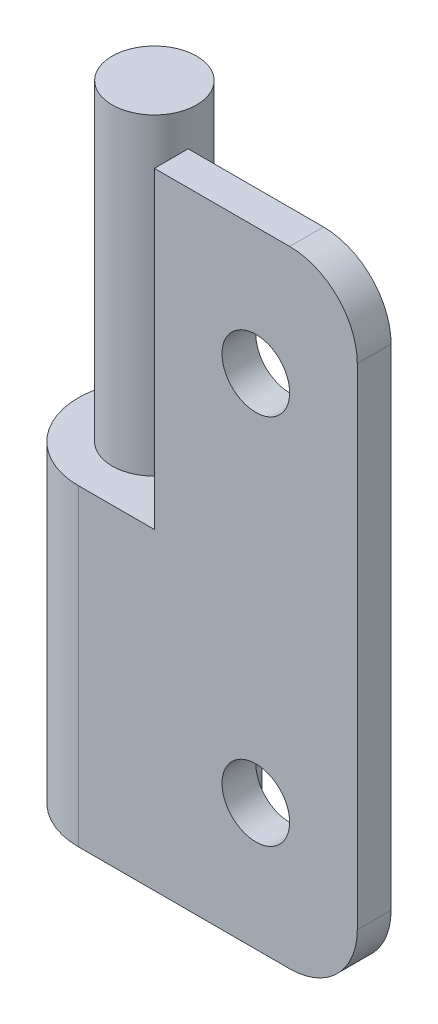
SolidWorks part; units mm, degrees
ref_plane "前视基准面" through (0, 0, 0) normal (0, 0, 1) x (1, 0, 0)
ref_plane "上视基准面" through (0, 0, 0) normal (0, 1, 0) x (1, 0, 0)
ref_plane "右视基准面" through (0, 0, 0) normal (1, 0, 0) x (0, 0, -1)
sketch "草图1" plane through (0, 0, 0) normal (0, 1, 0) x (1, 0, 0)
  line L0 (0, -4.5) -> (16.5, -4.5)
  line L1 (16.5, -4.5) -> (16.5, -2.5)
  line L2 (16.5, -2.5) -> (3.7417, -2.5)
  arc A0 (3.7417, -2.5) -> (0, -4.5) centre (0, 0) ccw
  circle A1 centre (0, 0) radius 2.5
  dimension "D1" = 9
  dimension "D2" = 5
  dimension "D3" = 16.5
  dimension "D4" = 2
extrude "凸台-拉伸1" add sketch "草图1" along normal blind 18.5
sketch "草图2" plane through (0, 18.5, 0) normal (0, 1, 0) x (1, 0, 0)
  line L0 (0, -4.5) -> (16.5, -4.5) construction
  line L1 (16.5, -2.5) -> (4.5, -2.5)
  line L2 (16.5, -2.5) -> (16.5, -4.5)
  line L3 (16.5, -4.5) -> (4.5, -4.5)
  line L4 (4.5, -2.5) -> (4.5, -4.5)
  dimension "D1" = 12
extrude "凸台-拉伸2" add sketch "草图2" along normal blind 18.5
sketch "草图3" plane through (0, 0, 2.5) normal (0, 0, -1) x (-1, 0, 0)
  line L0 (-16.5, 18.5) -> (-4.5, 18.5) construction
  line L1 (-16.5, 37) -> (-16.5, 0) construction
  circle A0 centre (-10.5, 7.5) radius 2
  circle A1 centre (-10.5, 29.5) radius 2
  dimension "D1" = 4
  dimension "D2" = 22
  dimension "D3" = 10.5
extrude "切除-拉伸1" cut sketch "草图3" against normal up to next
fillet "圆角1" radius 4 2 edges at (16.5, 37, 3.5) (16.5, 0, 3.5)
sketch "草图4" plane through (0, 0, 0) normal (0, -1, 0) x (1, 0, 0)
  circle A0 centre (0, 0) radius 2.5
extrude "凸台-拉伸3" add sketch "草图4" against normal blind 37
